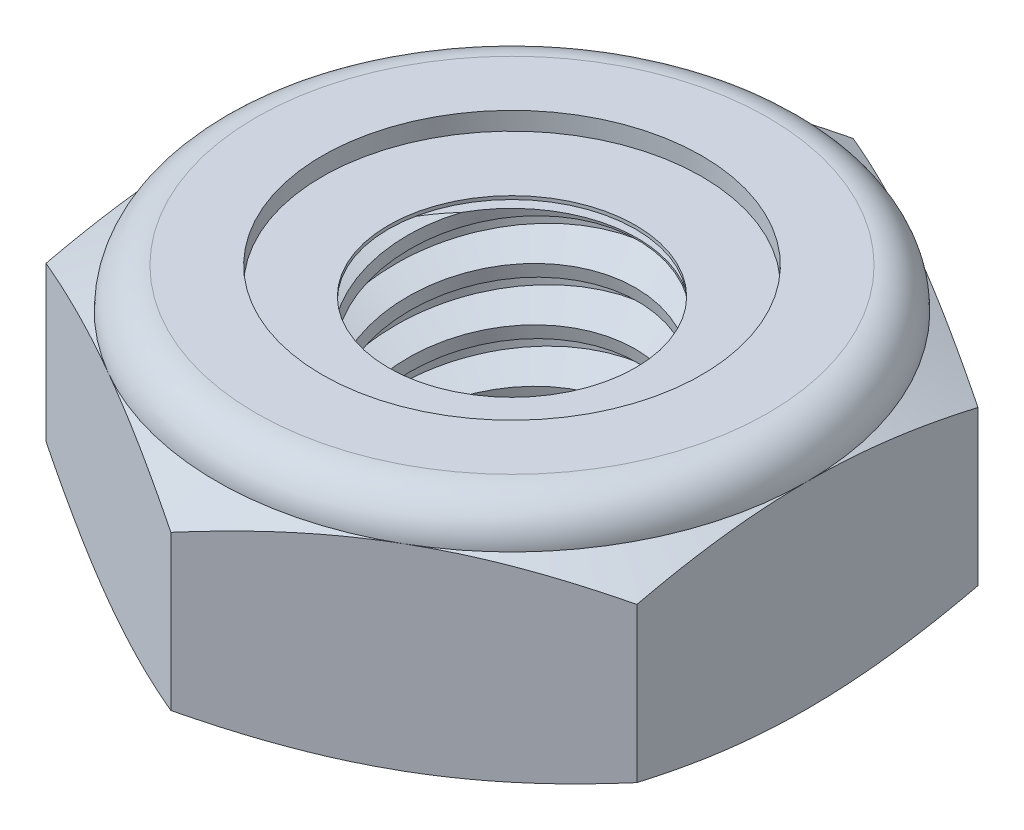
SolidWorks part; units mm, degrees
ref_plane "Front" through (0, 0, 0) normal (0, 0, 1) x (1, 0, 0)
ref_plane "Top" through (0, 0, 0) normal (0, 1, 0) x (1, 0, 0)
ref_plane "Right" through (0, 0, 0) normal (1, 0, 0) x (0, 0, -1)
sketch "Sketch1" plane through (0, 0, 0) normal (0, 1, 0) x (1, 0, 0)
  line L1 (0, 2.8868) -> (-2.5, 1.4434)
  line L2 (-2.5, 1.4434) -> (-2.5, -1.4434)
  line L3 (-2.5, -1.4434) -> (0, -2.8868)
  line L4 (0, -2.8868) -> (2.5, -1.4434)
  line L5 (2.5, -1.4434) -> (2.5, 1.4434)
  line L6 (2.5, 1.4434) -> (0, 2.8868)
  circle A0 centre (0, 0) radius 2.5 construction
  dimension "Hex Flats" = 5
extrude "Extrude1" add sketch "Sketch1" along normal blind 2
sketch "Sketch2" plane through (0, 0, 0) normal (1, 0, 0) x (0, 0, -1)
  line L0 (-1.25, 0) -> (-1.25, 2) construction
  line L1 (0, 0) -> (1.25, 0)
  line L2 (0, 0) -> (0, 2)
  line L3 (0, 2) -> (1.25, 2)
  line L4 (1.25, 0) -> (1.25, 2)
  line L5 (-1.4434, 2) -> (1.4434, 2) construction
  line L7 (0, -1.25) -> (0, 0) construction
  dimension "Thread Dia" = 2.5
revolve "Revolve1" add sketch "Sketch2" angle 360 about L7
sketch "Sketch3" plane through (0, 0, 0) normal (1, 0, 0) x (0, 0, -1)
  line L0 (1.25, 2) -> (-1.25, 2) construction
  line L1 (-1.25, 2) -> (-1.25, 1.55) construction
  line L2 (-1.25, 1.55) -> (1.25, 2) construction
  line L3 (1.25, 2) -> (1.26, 1.9446) construction
  line L4 (1.26, 1.9446) -> (1.3297, 1.5571)
  line L5 (1.3297, 1.5571) -> (1.0651, 1.6524)
  line L6 (1.0651, 1.6524) -> (1.0452, 1.7631)
  line L7 (1.0452, 1.7631) -> (1.26, 1.9446)
  line L8 (1.0551, 1.7077) -> (1.2948, 1.7509) construction
  line L9 (1.25, 2) -> (1.25, 1.7428) construction
  line L10 (1.25, 1.7428) -> (-1.25, 1.2928) construction
  line L11 (-1.25, 1.2928) -> (-1.25, 1.55) construction
  line L12 (-0.0868, 2) -> (0.0868, 1.0356) construction
  line L13 (-1.25, 0) -> (-1.25, 2) construction
  line L14 (0, 2) -> (1.25, 2) construction
  line L15 (1.25, 0) -> (1.25, 2) construction
  point P13 (0, 1.5178)
  dimension "D1" = 0.0563
  dimension "D2" = 0.1125
  dimension "Thread Pitch" = 0.45
  dimension "D4" = 60
  dimension "D5" = 0.45
revolve "Cut-Revolve1" cut sketch "Sketch3" angle 360 about L12
pattern_linear "LPattern1" count 4 spacing 0.45 along (0, -1, 0) count 2 spacing 0.45 along (0, 1, 0) of "Cut-Revolve1"
sketch "Sketch4" plane through (0, 0, 0) normal (1, 0, 0) x (0, 0, -1)
  line L0 (0, 2) -> (1.25, 2)
  line L1 (1.25, 2) -> (1.0452, 1.9045)
  line L2 (1.0452, 1.9045) -> (1.0452, 0.0955)
  line L3 (1.0452, 0.0955) -> (1.25, 0)
  line L4 (1.25, 0) -> (0, 0)
  line L5 (0, 0) -> (0, 2)
  line L6 (1.25, 0) -> (1.25, 2) construction
  line L7 (0, 2) -> (1.25, 2) construction
  line L8 (0, 0) -> (1.25, 0) construction
  line L9 (0, 0) -> (0, 2) construction
  line L10 (0, 2) -> (0, 2.226) construction
  dimension "D1" = 25
revolve "Cut-Revolve2" cut sketch "Sketch4" angle 360 about L10
combine bodies "Combine1" operation type subtract main body 112 bodies to subtract 111
sketch "Sketch5" plane through (0, 0, 0) normal (1, 0, 0) x (0, 0, -1)
  line L0 (0, 0) -> (2.5, 0)
  line L1 (2.5, 0) -> (2.8868, 0.1803)
  line L2 (2.8868, 0.1803) -> (2.8868, 1.4863)
  line L3 (2.8868, 1.4863) -> (2.5, 1.6667)
  line L4 (2.1667, 2) -> (2.1667, 3.27)
  line L5 (2.1667, 3.27) -> (4.1568, 3.27)
  line L6 (4.1568, 3.27) -> (4.1568, -1.27)
  line L7 (4.1568, -1.27) -> (0, -1.27)
  line L8 (0, -1.27) -> (0, 0)
  line L9 (2.5, 1.6667) -> (2.5, 0) construction
  line L10 (0, 0) -> (1.25, 0) construction
  line L13 (2.8868, 0.8333) -> (4.1568, 0.8333) construction
  line L14 (2.8868, 2) -> (2.8868, 0) construction
  line L15 (0, 0) -> (0, 3.27) construction
  line L20 (0, 3.27) -> (2.1667, 3.27) construction
  line L22 (0, 2) -> (1.25, 2) construction
  arc A0 (2.5, 1.6667) -> (2.1667, 2) centre (2.1667, 1.6667) ccw
  dimension "D1" = 25
  dimension "D2" = 1.27
  dimension "D3" = 2
  dimension "D4" = 0.3333
revolve "Cut-Revolve3" cut sketch "Sketch5" angle 360 about L15
sketch "Sketch6" plane through (0, 0, 0) normal (1, 0, 0) x (0, 0, -1)
  line L0 (0, 1.6667) -> (2.3476, 1.6667)
  line L1 (2.1667, 1.8476) -> (1.6059, 1.8476)
  line L2 (0, 3.27) -> (0, 1.6667)
  line L3 (1.6059, 3.27) -> (0, 3.27)
  line L4 (0, 3.27) -> (2.1667, 3.27) construction
  line L5 (0, 0) -> (0, 3.27) construction
  line L6 (0, 3.27) -> (0, 44.323) construction
  line L7 (1.6059, 1.8476) -> (1.6059, 3.27)
  line L8 (2.1667, 2) -> (2.1667, 1.8476) construction
  line L9 (1.6059, 1.8476) -> (1.0452, 1.8476) construction
  line L10 (1.0452, 1.8476) -> (1.0452, 1.9045) construction
  arc A0 (2.3476, 1.6667) -> (2.1667, 1.8476) centre (2.1667, 1.6667) ccw
  arc A1 (2.5, 1.6667) -> (2.1667, 2) centre (2.1667, 1.6667) ccw construction
  dimension "D1" = 0.1524
revolve "Cut-Revolve4" cut sketch "Sketch6" angle 360 about L6
sketch "Sketch7" plane through (0, 0, 0) normal (1, 0, 0) x (0, 0, -1)
  line L0 (1.0452, 1.7429) -> (2.2385, 1.7429)
  line L1 (2.1667, 1.7714) -> (1.0452, 1.7714)
  line L2 (1.0452, 1.7714) -> (1.0452, 1.7429)
  line L3 (1.0452, 1.7429) -> (0, 1.7429) construction
  line L4 (0, 1.7429) -> (0, 1.7714) construction
  line L5 (0, 1.7714) -> (1.0452, 1.7714) construction
  line L6 (1.0452, 1.7429) -> (1.0452, 1.6667) construction
  line L7 (0, 1.6667) -> (2.3476, 1.6667) construction
  line L8 (2.1667, 1.7714) -> (2.1667, 1.8476) construction
  arc A0 (2.2385, 1.7429) -> (2.1667, 1.7714) centre (2.1667, 1.6667) ccw
  arc A2 (2.3476, 1.6667) -> (2.1667, 1.8476) centre (2.1667, 1.6667) ccw construction
  dimension "D1" = 0.0762
revolve "Revolve2" add sketch "Sketch7" angle 360 about L4
equation "\"D1@Sketch3\"=\"Thread Pitch@Sketch3\"/8"
equation "\"D2@Sketch3\"=\"Thread Pitch@Sketch3\"/4"
equation "\"D5@Sketch3\"=\"Thread Pitch@Sketch3\""
equation "\"D4@LPattern1\"=\"Thread Pitch@Sketch3\""
equation "\"D3@LPattern1\"=\"Thread Pitch@Sketch3\""
equation "\"D1@LPattern1\"=\"Height@Extrude1\"/\"Thread Pitch@Sketch3\""
equation "\"D4@Sketch5\"=\"Height@Extrude1\"/6"
